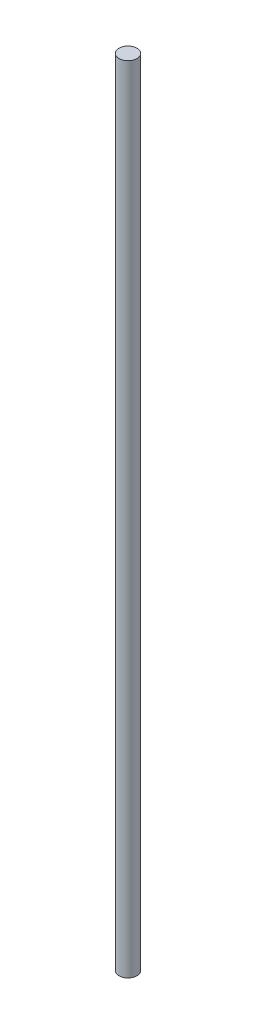
SolidWorks part; units mm, degrees
material "Aluminum MEGR 2156"
ref_plane "Front Plane" through (0, 0, 0) normal (0, 0, 1) x (1, 0, 0)
ref_plane "Top Plane" through (0, 0, 0) normal (0, 1, 0) x (1, 0, 0)
ref_plane "Right Plane" through (0, 0, 0) normal (1, 0, 0) x (0, 0, -1)
sketch "Sketch1" plane through (0, 0, 0) normal (0, 1, 0) x (1, 0, 0)
  circle A0 centre (0, 0) radius 3.175
  dimension "D1" = 6.35
extrude "Boss-Extrude1" add sketch "Sketch1" along normal blind 280.416
equation "\"Load\"= 400'lbf"
equation "\"Elastic_Modulus\"= 10000000'psi"
equation "\"Max_Deflection\" = .009in'in"
equation "\"Diameter\"= .250in'in"
equation "\"Area\"= ( pi * \"Diameter\" ^ 2 ) / 4'in^2"
equation "\"Length\" = ( ( \"Max_Deflection\" * \"Area\" * \"Elastic_Modulus\" ) / \"Load\" )'in"
